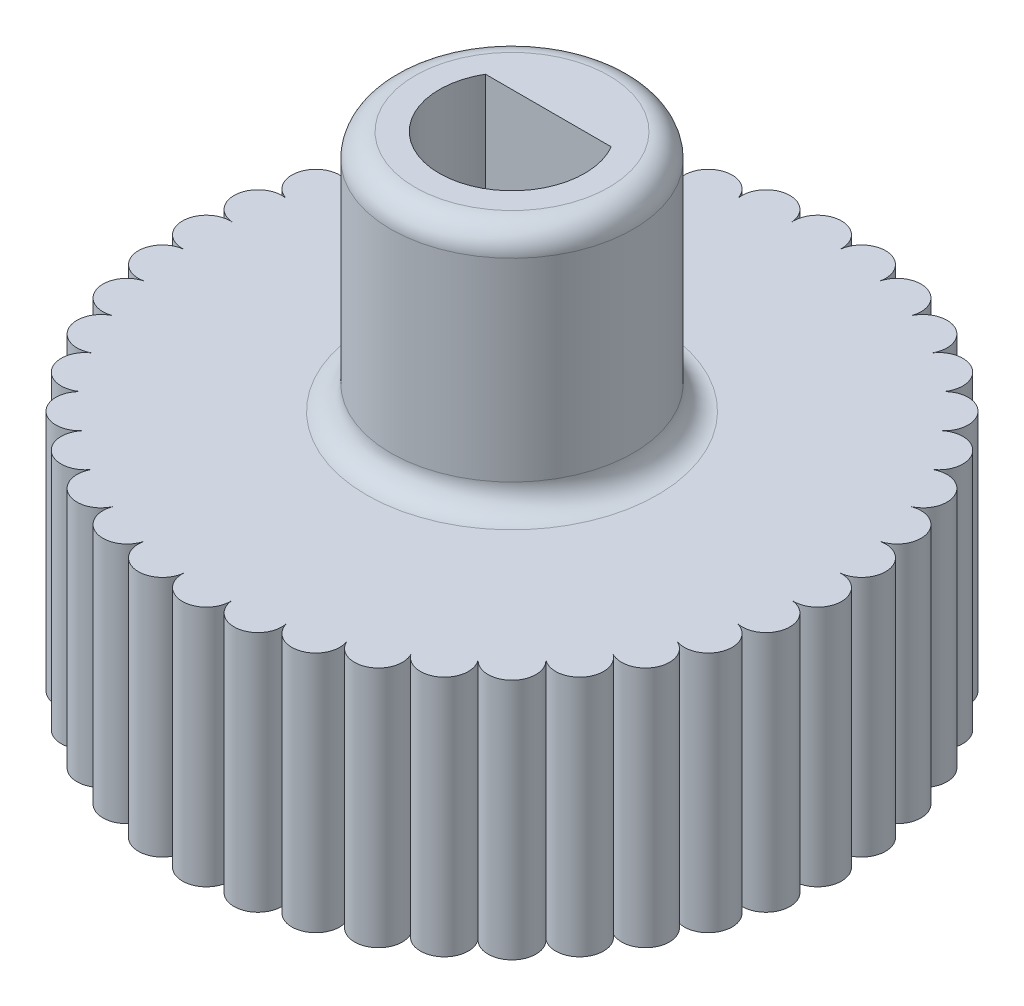
SolidWorks part; units mm, degrees
ref_plane "Front Plane" through (0, 0, 0) normal (0, 0, 1) x (1, 0, 0)
ref_plane "Top Plane" through (0, 0, 0) normal (0, 1, 0) x (1, 0, 0)
ref_plane "Right Plane" through (0, 0, 0) normal (1, 0, 0) x (0, 0, -1)
sketch "Sketch1" plane through (0, 0, 0) normal (0, 1, 0) x (1, 0, 0)
  arc A1 (0.9867, 12.5377) -> (-0.9867, 12.5377) centre (0, 12.6153) ccw
  arc A2 (2.9359, 12.2289) -> (0.9867, 12.5377) centre (1.9735, 12.46) ccw
  arc A3 (4.8128, 11.6191) -> (2.9359, 12.2289) centre (3.8983, 11.9979) ccw
  arc A4 (6.5712, 10.7232) -> (4.8128, 11.6191) centre (5.7272, 11.2403) ccw
  arc A5 (8.1677, 9.5632) -> (6.5712, 10.7232) centre (7.4151, 10.206) ccw
  arc A6 (9.5632, 8.1677) -> (8.1677, 9.5632) centre (8.9204, 8.9204) ccw
  arc A7 (10.7232, 6.5712) -> (9.5632, 8.1677) centre (10.206, 7.4151) ccw
  arc A8 (11.6191, 4.8128) -> (10.7232, 6.5712) centre (11.2403, 5.7272) ccw
  arc A9 (12.2289, 2.9359) -> (11.6191, 4.8128) centre (11.9979, 3.8983) ccw
  arc A10 (12.5377, 0.9867) -> (12.2289, 2.9359) centre (12.46, 1.9735) ccw
  arc A11 (12.5377, -0.9867) -> (12.5377, 0.9867) centre (12.6153, 0) ccw
  arc A12 (12.2289, -2.9359) -> (12.5377, -0.9867) centre (12.46, -1.9735) ccw
  arc A13 (11.6191, -4.8128) -> (12.2289, -2.9359) centre (11.9979, -3.8983) ccw
  arc A14 (10.7232, -6.5712) -> (11.6191, -4.8128) centre (11.2403, -5.7272) ccw
  arc A15 (9.5632, -8.1677) -> (10.7232, -6.5712) centre (10.206, -7.4151) ccw
  arc A16 (8.1677, -9.5632) -> (9.5632, -8.1677) centre (8.9204, -8.9204) ccw
  arc A17 (6.5712, -10.7232) -> (8.1677, -9.5632) centre (7.4151, -10.206) ccw
  arc A18 (4.8128, -11.6191) -> (6.5712, -10.7232) centre (5.7272, -11.2403) ccw
  arc A19 (2.9359, -12.2289) -> (4.8128, -11.6191) centre (3.8983, -11.9979) ccw
  arc A20 (0.9867, -12.5377) -> (2.9359, -12.2289) centre (1.9735, -12.46) ccw
  arc A21 (-0.9867, -12.5377) -> (0.9867, -12.5377) centre (0, -12.6153) ccw
  arc A22 (-2.9359, -12.2289) -> (-0.9867, -12.5377) centre (-1.9735, -12.46) ccw
  arc A23 (-4.8128, -11.6191) -> (-2.9359, -12.2289) centre (-3.8983, -11.9979) ccw
  arc A24 (-6.5712, -10.7232) -> (-4.8128, -11.6191) centre (-5.7272, -11.2403) ccw
  arc A25 (-8.1677, -9.5632) -> (-6.5712, -10.7232) centre (-7.4151, -10.206) ccw
  arc A26 (-9.5632, -8.1677) -> (-8.1677, -9.5632) centre (-8.9204, -8.9204) ccw
  arc A27 (-10.7232, -6.5712) -> (-9.5632, -8.1677) centre (-10.206, -7.4151) ccw
  arc A28 (-11.6191, -4.8128) -> (-10.7232, -6.5712) centre (-11.2403, -5.7272) ccw
  arc A29 (-12.2289, -2.9359) -> (-11.6191, -4.8128) centre (-11.9979, -3.8983) ccw
  arc A30 (-12.5377, -0.9867) -> (-12.2289, -2.9359) centre (-12.46, -1.9735) ccw
  arc A31 (-12.5377, 0.9867) -> (-12.5377, -0.9867) centre (-12.6153, 0) ccw
  arc A32 (-12.2289, 2.9359) -> (-12.5377, 0.9867) centre (-12.46, 1.9735) ccw
  arc A33 (-11.6191, 4.8128) -> (-12.2289, 2.9359) centre (-11.9979, 3.8983) ccw
  arc A34 (-10.7232, 6.5712) -> (-11.6191, 4.8128) centre (-11.2403, 5.7272) ccw
  arc A35 (-9.5632, 8.1677) -> (-10.7232, 6.5712) centre (-10.206, 7.4151) ccw
  arc A36 (-8.1677, 9.5632) -> (-9.5632, 8.1677) centre (-8.9204, 8.9204) ccw
  arc A37 (-6.5712, 10.7232) -> (-8.1677, 9.5632) centre (-7.4151, 10.206) ccw
  arc A38 (-4.8128, 11.6191) -> (-6.5712, 10.7232) centre (-5.7272, 11.2403) ccw
  arc A39 (-2.9359, 12.2289) -> (-4.8128, 11.6191) centre (-3.8983, 11.9979) ccw
  arc A40 (-0.9867, 12.5377) -> (-2.9359, 12.2289) centre (-1.9735, 12.46) ccw
  dimension "D1" = 40
extrude "Boss-Extrude2" add sketch "Sketch1" along normal blind 10
sketch "Sketch2" plane through (0, 10, 0) normal (0, 1, 0) x (1, 0, 0)
  line L0 (-2.5981, 1.5) -> (2.5981, 1.5)
  line L1 (0, -3) -> (15.8442, -3) construction
  arc A0 (-2.5981, 1.5) -> (2.5981, 1.5) centre (0, 0) ccw
  circle A1 centre (0, 0) radius 5
  point P7 (0, 0)
  point P9 (0, 0)
  point P10 (0, 0)
  dimension "D1" = 6
  dimension "D2" = 10
  dimension "D3" = 4.5
extrude "Boss-Extrude3" add sketch "Sketch2" along normal blind 10
fillet "Fillet5" radius 1 1 edges at (0, 20, 5)
fillet "Fillet7" radius 1 1 edges at (0, 10, 5)
